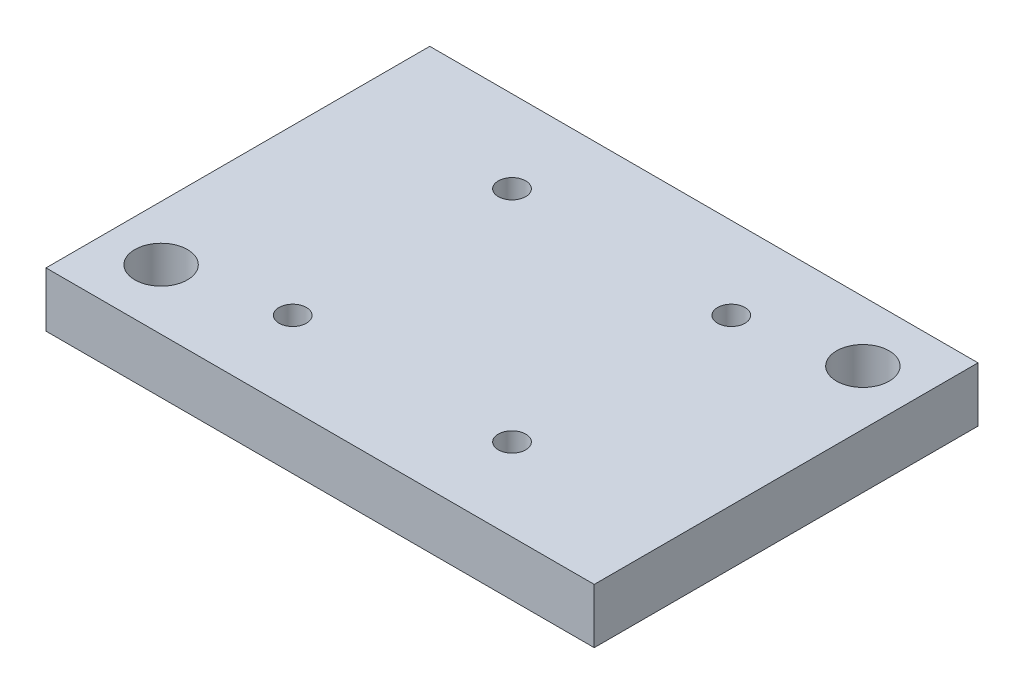
SolidWorks part; units mm, degrees
ref_plane "Front Plane" through (0, 0, 0) normal (0, 0, 1) x (1, 0, 0)
ref_plane "Top Plane" through (0, 0, 0) normal (0, 1, 0) x (1, 0, 0)
ref_plane "Right Plane" through (0, 0, 0) normal (1, 0, 0) x (0, 0, -1)
sketch "Esquisse1" plane through (0, 0, 0) normal (0, 1, 0) x (1, 0, 0)
  line L1 (-18.4286, 15.1429) -> (31.5714, 15.1429)
  line L2 (-18.4286, 15.1429) -> (-18.4286, -19.8571)
  line L3 (-18.4286, -19.8571) -> (31.5714, -19.8571)
  line L4 (31.5714, 15.1429) -> (31.5714, -19.8571)
  dimension "D1" = 35
  dimension "D2" = 50
extrude "Boss.-Extru.1" add sketch "Esquisse1" along normal blind 5
sketch "Esquisse2" plane through (0, 5, 0) normal (0, 1, 0) x (1, 0, 0)
  line L0 (6.5714, -2.3571) -> (6.5714, 7.6429) construction
  line L3 (6.5714, -2.3571) -> (-3.4286, -2.3571) construction
  line L4 (-3.4286, -2.3571) -> (-3.4286, 7.6429) construction
  line L5 (-3.4286, 7.6429) -> (16.5714, 7.6429) construction
  line L6 (16.5714, 7.6429) -> (16.5714, -12.3571) construction
  line L7 (16.5714, -12.3571) -> (-3.4286, -12.3571) construction
  line L8 (-3.4286, -12.3571) -> (-3.4286, -2.3571) construction
  line L9 (6.5714, -2.3571) -> (6.5714, -19.8571) construction
  line L10 (-18.4286, -19.8571) -> (31.5714, -19.8571) construction
  point P9 (-3.4286, 7.6429)
  point P10 (16.5714, 7.6429)
  point P11 (16.5714, -12.3571)
  point P12 (-3.4286, -12.3571)
  point P18 (-3.4286, 7.6429)
  point P22 (-3.4286, -12.3571)
  point P26 (16.5714, -12.3571)
  point P30 (16.5714, 7.6429)
  dimension "D1" = 10
  dimension "D2" = 10
  dimension "D3" = 20
  dimension "D4" = 20
  dimension "D5" = 17.5
hole_wizard "Trou pour taraudage pour trou taraudé M33" positions "Esquisse2" profile "Esquisse3" hole size "M3" standard "ISO" end condition through all
sketch "Esquisse3" plane through (16.5714, 5, -7.6429) normal (1, 0, 0) x (0, 0, 1)
  line L0 (0, 0) -> (0, 5)
  line L1 (0, 5) -> (1.25, 5)
  line L2 (1.25, 5) -> (1.25, 0)
  line L5 (1.25, 0) -> (0, 0)
  line L11 (0, -6.35) -> (0, 107.95) construction
  dimension "Diamètre du perçage jusqu'au prochain" = 2.5
  dimension "Profondeur du perçage jusqu'au prochain" = 5
sketch "Esquisse4" plane through (0, 5, 0) normal (0, 1, 0) x (1, 0, 0)
  line L0 (6.5714, -2.3571) -> (26.5714, -2.3571) construction
  line L1 (6.5714, -2.3571) -> (-13.4286, -2.3571) construction
  line L2 (-13.4286, -2.3571) -> (-13.4286, -14.3571) construction
  line L3 (26.5714, -2.3571) -> (26.5714, 9.6429) construction
  point P5 (-13.4286, -14.3571)
  point P6 (26.5714, 9.6429)
  point P10 (-13.4286, -14.3571)
  point P14 (26.5714, 9.6429)
  dimension "D1" = 20
  dimension "D2" = 20
  dimension "D3" = 12
  dimension "D4" = 12
hole_wizard "Dégagement M43" positions "Esquisse4" profile "Esquisse5" hole size "M4" standard "ISO" end condition through all
sketch "Esquisse5" plane through (26.5714, 5, -9.6429) normal (1, 0, 0) x (0, 0, 1)
  line L0 (0, 0) -> (0, 5)
  line L1 (0, 5) -> (2.4, 5)
  line L2 (2.4, 5) -> (2.4, 0)
  line L5 (2.4, 0) -> (0, 0)
  line L11 (0, -6.35) -> (0, 107.95) construction
  dimension "Diamètre du perçage jusqu'au prochain" = 4.8
  dimension "Profondeur du perçage jusqu'au prochain" = 5
